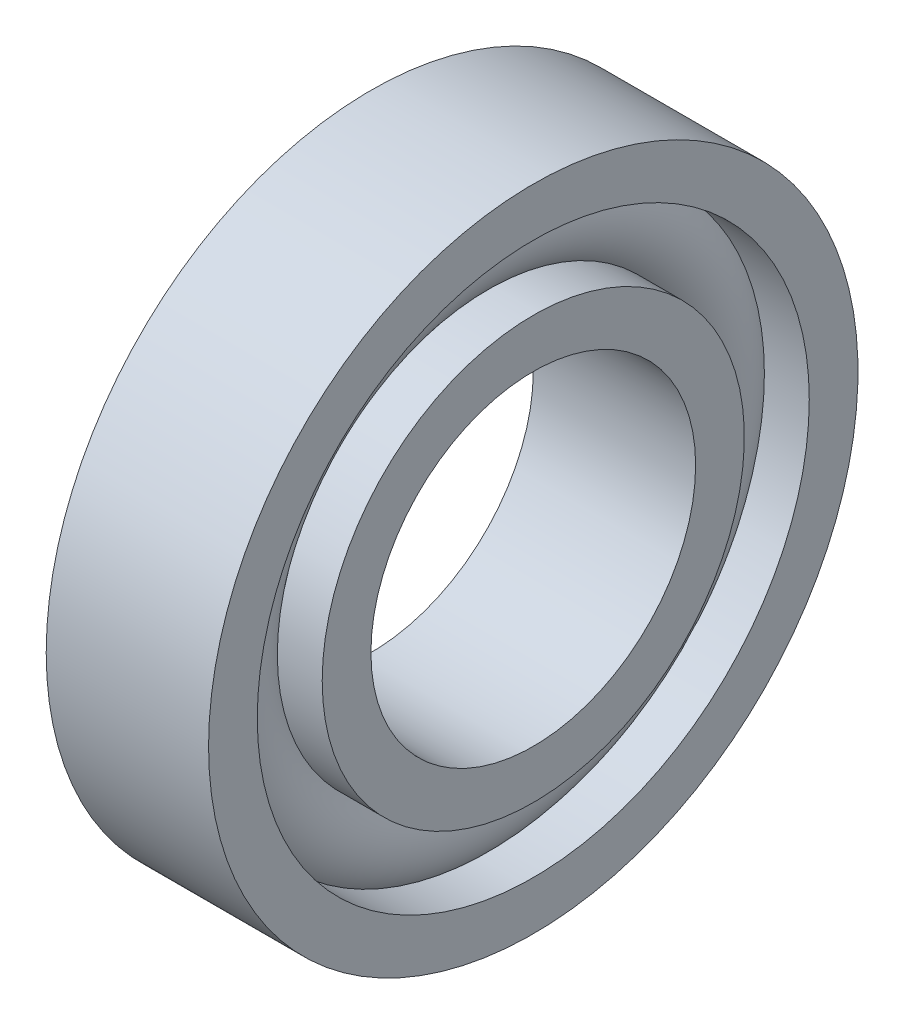
SolidWorks part; units mm, degrees
material "1.2083 (X40Cr14)"
ref_plane "Plan de face" through (0, 0, 0) normal (0, 0, 1) x (1, 0, 0)
ref_plane "Plan de dessus" through (0, 0, 0) normal (0, 1, 0) x (1, 0, 0)
ref_plane "Plan de droite" through (0, 0, 0) normal (1, 0, 0) x (0, 0, -1)
sketch "Esquisse1" plane through (0, 0, 0) normal (0, 0, 1) x (1, 0, 0)
  line L0 (-2, 4) -> (2, 4)
  line L1 (2, 4) -> (2, 5.2)
  line L2 (2, 5.2) -> (0.8944, 5.2)
  line L3 (0, 4) -> (0, 8) construction
  line L4 (-2, 0) -> (2, 0) construction
  line L5 (0, 6) -> (1.2, 6) construction
  line L6 (-2, 5.2) -> (-0.8944, 5.2)
  line L7 (-2, 4) -> (-2, 5.2)
  line L8 (-2, 8) -> (-2, 6.8)
  line L9 (-2, 6.8) -> (-0.8944, 6.8)
  line L10 (2, 6.8) -> (0.8944, 6.8)
  line L11 (2, 8) -> (2, 6.8)
  line L12 (-2, 8) -> (2, 8)
  arc A0 (0.8944, 5.2) -> (0.8944, 6.8) centre (0, 6) ccw
  arc A1 (-0.8944, 5.2) -> (-0.8944, 6.8) centre (0, 6) cw
  dimension "D5" = 1.2
  dimension "D1" = 8
  dimension "D2" = 16
  dimension "D3" = 4
  dimension "D4" = 1.2
revolve "Révolution1" add sketch "Esquisse1" angle 360 about L4
